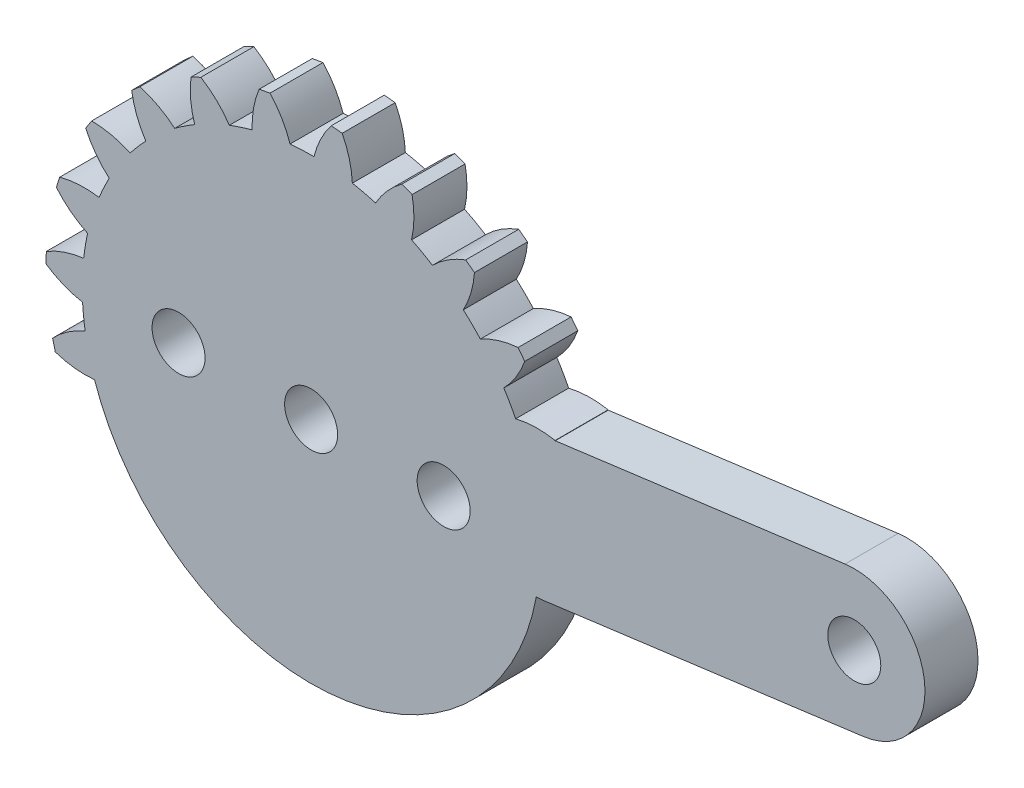
SolidWorks part; units mm, degrees
ref_plane "Front Plane" through (0, 0, 0) normal (0, 0, 1) x (1, 0, 0)
ref_plane "Top Plane" through (0, 0, 0) normal (0, 1, 0) x (1, 0, 0)
ref_plane "Right Plane" through (0, 0, 0) normal (1, 0, 0) x (0, 0, -1)
sketch "Sketch1" plane through (0, 0, 0) normal (0, 0, 1) x (1, 0, 0)
  line L0 (-15.3923, 0) -> (-14.8209, 0) construction
  line L1 (30.73, 4.05) -> (14.8179, 1.9551) construction
  line L2 (31.2521, 0.0842) -> (13.1979, -2.2927)
  line L3 (30.2079, 8.0158) -> (13.809, 5.8568)
  line L4 (0, 12.95) -> (0, -22.4393) construction
  line L5 (-34.6236, 0) -> (-14.8209, 0) construction
  line L6 (0, 0) -> (1.7567, 13.3438) construction
  line L7 (0, 0) -> (17.018, 13.0584) construction
  line L8 (12.0865, 8.8835) -> (11.709, 9.3754)
  line L9 (13.809, 5.8568) -> (13.8043, 5.8687)
  line L10 (-13.459, 0) -> (8.2812, 0) construction
  line L11 (-13.459, 0) -> (51.7251, 0) construction
  line L12 (1.9165, 14.5572) -> (2.6294, 19.9723) construction
  line L21 (-14.6251, -3.3328) -> (-14.4748, -3.9343)
  line L22 (-14.9819, 0.7366) -> (-14.9995, 0.1168)
  line L23 (-14.2276, 4.7513) -> (-14.4118, 4.1593)
  line L24 (-12.4181, 8.4137) -> (-12.7552, 7.8933)
  line L25 (-9.6876, 11.4521) -> (-10.1526, 11.0419)
  line L26 (-6.2387, 13.6411) -> (-6.797, 13.3716)
  line L27 (-2.327, 14.8184) -> (-2.9374, 14.7096)
  line L28 (1.7573, 14.8967) -> (1.1402, 14.9566)
  line L29 (5.7112, 13.8702) -> (5.1331, 14.0944)
  line L30 (9.2415, 11.815) -> (8.7454, 12.1868)
  line L33 (14.9427, 1.3103) -> (14.8757, 1.9267) [skipped]
  line L34 (14.7421, -2.7697) -> (14.8439, -2.1582) [skipped]
  line L35 (13.4481, -6.6444) -> (13.7112, -6.083) [skipped]
  line L36 (11.1568, -10.0263) -> (11.5616, -9.5567) [skipped]
  line L37 (8.038, -12.6645) -> (8.5545, -12.3215) [skipped]
  line L38 (4.3231, -14.3635) -> (4.913, -14.1726) [skipped]
  line L39 (0.2875, -14.9972) -> (0.9071, -14.9725) [skipped]
  line L40 (-3.7693, -14.5187) -> (-3.1661, -14.662) [skipped]
  line L41 (-7.5466, -12.9633) -> (-7.0045, -13.2641) [skipped]
  line L42 (-10.7643, -10.4466) -> (-10.3234, -10.8825) [skipped]
  line L43 (-13.1835, -7.155) -> (-12.8766, -7.6937) [skipped]
  circle A0 centre (0, 0) radius 1.5
  arc A1 (0.1616, 12.949) -> (-1.1918, 12.895) centre (0, 0) ccw
  arc A2 (12.0865, 8.8835) -> (11.709, 9.3754) centre (0, 0) ccw
  arc A3 (31.2521, 0.0842) -> (30.2079, 8.0158) centre (30.73, 4.05) ccw
  circle A5 centre (7.5, 0) radius 1.5
  circle A6 centre (-7.5, 0) radius 1.5
  arc A10 (9.5739, 8.7202) -> (11.709, 9.3754) centre (12.1467, 4.1425) cw
  arc A11 (10.901, 6.9907) -> (12.0865, 8.8835) centre (7.1452, 10.6606) ccw
  arc A12 (11.5716, 5.8139) -> (10.901, 6.9907) centre (0, 0) ccw
  arc A13 (11.5716, 5.8139) -> (13.8043, 5.8687) centre (12.8139, 0.7118) cw
  arc A14 (14.7633, -2.0866) -> (14.8439, -2.1582) centre (11.3183, -6.0497) cw
  arc A15 (-6.2387, 13.6411) -> (-6.797, 13.3716) centre (0, 0) ccw
  circle A16 centre (30.73, 4.05) radius 1.5
  arc A17 (13.8093, 5.8569) -> (13.8043, 5.8687) centre (0, 0) ccw
  arc A18 (14.8757, 1.9267) -> (14.8711, 1.9621) centre (0, 0) ccw
  arc A19 (9.2415, 11.815) -> (8.7454, 12.1868) centre (0, 0) ccw
  arc A20 (5.7112, 13.8702) -> (5.1331, 14.0944) centre (0, 0) ccw
  arc A21 (14.8439, -2.1582) -> (14.8559, -2.0744) centre (0, 0) ccw
  arc A28 (-14.6251, -3.3328) -> (-14.4748, -3.9343) centre (0, 0) ccw
  arc A29 (-14.9819, 0.7366) -> (-15, 0) centre (0, 0) ccw
  arc A30 (3.6492, 12.4252) -> (2.3314, 12.7384) centre (0, 0) ccw
  arc A31 (-14.2276, 4.7513) -> (-14.4118, 4.1593) centre (0, 0) ccw
  arc A32 (6.8662, 10.9799) -> (5.6818, 11.637) centre (0, 0) ccw
  arc A33 (9.5739, 8.7202) -> (8.6107, 9.6726) centre (0, 0) ccw
  arc A34 (-9.6876, 11.4521) -> (-10.1526, 11.0419) centre (0, 0) ccw
  arc A35 (12.7393, -2.3264) -> (13.1979, -2.2927) centre (12.6758, 1.6731) ccw
  arc A36 (-12.7837, -2.069) -> (-14.6251, -3.3328) centre (-10.8008, -6.9314) ccw
  arc A37 (-12.2555, -4.184) -> (-14.4748, -3.9343) centre (-12.7915, 1.0397) cw
  arc A38 (-12.8678, 1.4567) -> (-14.9819, 0.7366) centre (-12.2704, -3.7603) ccw
  arc A39 (-12.9298, -0.7224) -> (-14.9995, 0.1168) centre (-12.0366, 4.4522) cw
  arc A40 (-11.9976, 4.8744) -> (-14.2276, 4.7513) centre (-12.8299, -0.3104) ccw
  arc A41 (-12.6453, 2.7928) -> (-14.4118, 4.1593) centre (-10.3891, 7.5346) cw
  arc A42 (-10.2376, 7.9306) -> (-12.4181, 8.4137) centre (-12.4379, 3.1626) ccw
  arc A43 (-11.4229, 6.1009) -> (-12.7552, 7.8933) centre (-7.971, 10.0581) cw
  arc A44 (-7.7183, 10.3985) -> (-9.6876, 11.4521) centre (-11.1234, 6.401) ccw
  arc A45 (-9.3533, 8.9565) -> (-10.1526, 11.0419) centre (-4.9618, 11.8357) cw
  arc A46 (-4.6266, 12.0953) -> (-6.2387, 13.6411) centre (-8.9839, 9.1647) ccw
  arc A47 (-6.59, 11.1479) -> (-6.797, 13.3716) centre (-1.5846, 12.7355) cw
  arc A48 (-1.1918, 12.895) -> (-2.327, 14.8184) centre (-6.1782, 11.2487) ccw
  arc A49 (-3.3379, 12.5124) -> (-2.9374, 14.7096) centre (1.9102, 12.6907) cw
  arc A50 (2.3314, 12.7384) -> (1.7573, 14.8967) centre (-2.9142, 12.4984) ccw
  arc A51 (0.1616, 12.949) -> (1.1402, 14.9566) centre (5.2632, 11.7047) cw
  arc A52 (5.6818, 11.637) -> (5.7112, 13.8702) centre (0.5659, 12.8212) ccw
  arc A53 (3.6492, 12.4252) -> (5.1331, 14.0944) centre (8.226, 9.8507) cw
  arc A54 (8.6107, 9.6726) -> (9.2415, 11.815) centre (4.004, 12.1931) ccw
  arc A55 (6.8662, 10.9799) -> (8.7454, 12.1868) centre (10.5786, 7.2661) cw
  arc A56 (-3.3379, 12.5124) -> (-4.6266, 12.0953) centre (0, 0) ccw
  arc A57 (-6.59, 11.1479) -> (-7.7183, 10.3985) centre (0, 0) ccw
  arc A58 (-9.3533, 8.9565) -> (-10.2376, 7.9306) centre (0, 0) ccw
  arc A59 (-11.4229, 6.1009) -> (-11.9976, 4.8744) centre (0, 0) ccw
  arc A60 (-12.6453, 2.7928) -> (-12.8678, 1.4567) centre (0, 0) ccw
  arc A61 (-12.9298, -0.7224) -> (-12.7837, -2.069) centre (0, 0) ccw
  arc A62 (-12.2555, -4.184) -> (12.7393, -2.3264) centre (0, 0) ccw
  arc A63 (-11.7514, -5.4413) -> (-12.1518, -5.7859) centre (-8.5302, -9.5884) ccw [skipped]
  arc A64 (-10.6722, -7.3354) -> (-11.1728, -7.5041) centre (-12.5976, -2.45) cw [skipped]
  arc A65 (-9.8476, -8.41) -> (-10.1402, -8.8499) centre (-5.627, -11.5343) ccw [skipped]
  arc A66 (-8.7339, -10.2402) -> (-10.3234, -10.8825) centre (-11.4695, -5.7579) cw [skipped]
  arc A67 (-7.3765, -11.2575) -> (-7.5466, -12.9633) centre (-2.3064, -12.6247) ccw [skipped]
  arc A68 (12.3829, 3.7904) -> (12.8265, 4.0774) centre (9.7564, 8.3376) ccw [skipped]
  arc A69 (14.8179, 1.9551) -> (14.8757, 1.9267) centre (12.5308, -2.7718) cw
  arc A70 (12.711, 2.4763) -> (13.2375, 2.4316) centre (12.5308, -2.7718) cw [skipped]
  arc A71 (12.9463, 0.309) -> (13.4509, 0.4656) centre (11.6441, 5.3961) ccw [skipped]
  arc A72 (12.9078, -1.0449) -> (13.4026, -1.23) centre (11.3183, -6.0497) cw [skipped]
  arc A73 (12.5496, -3.1953) -> (13.0777, -3.1806) centre (12.6681, 2.0545) ccw [skipped]
  arc A74 (-5.3072, -11.8126) -> (-5.6472, -12.2169) centre (-9.4907, -8.6388) cw [skipped]
  arc A75 (-4.0443, -12.3023) -> (-4.0657, -12.8302) centre (1.1852, -12.7788) ccw [skipped]
  arc A76 (-1.9234, -12.8064) -> (-2.1418, -13.2875) centre (-6.808, -10.879) cw [skipped]
  arc A77 (12.1472, -4.4887) -> (12.5738, -4.8004) centre (9.2664, -8.879) cw [skipped]
  arc A78 (11.2221, -6.4627) -> (11.7346, -6.591) centre (12.7527, -1.4395) ccw [skipped]
  arc A79 (10.8124, -8.0147) -> (11.5616, -9.5567) centre (6.5272, -11.0498) cw [skipped]
  arc A80 (9.0624, -9.2507) -> (9.5213, -9.5126) centre (11.8914, -4.8268) ccw [skipped]
  arc A81 (8.2491, -10.6347) -> (8.5545, -12.3215) centre (3.304, -12.4011) cw [skipped]
  arc A82 (6.2305, -11.3527) -> (6.6017, -11.7286) centre (10.1482, -7.856) ccw [skipped]
  arc A83 (5.074, -12.4659) -> (4.913, -14.1726) centre (-0.1643, -12.8326) cw [skipped]
  arc A84 (3.1926, -13.0748) -> (4.3231, -14.3635) centre (7.6523, -10.3026) ccw [skipped]
  arc A85 (-0.5752, -12.9372) -> (-0.4534, -13.4513) centre (4.5889, -11.9852) ccw [skipped]
  arc A86 (1.6031, -12.8504) -> (1.5226, -13.3726) centre (-3.6204, -12.3124) cw [skipped]
  arc A87 (-12.4181, 8.4137) -> (-12.7552, 7.8933) centre (0, 0) ccw
  arc A88 (1.9579, 14.8717) -> (1.1402, 14.9566) centre (0, 0) ccw
  arc A89 (-2.327, 14.8184) -> (-2.9374, 14.7096) centre (0, 0) ccw
  arc A91 (0.3125, 13.4553) -> (0, 13.459) centre (0, 0) ccw construction
  point P9 (21.7029, 2.8616)
  point P26 (0, 0)
  dimension "D1" = 3
  dimension "D2" = 25.9
  dimension "D3" = 30
  dimension "D12" = 37.5
  dimension "D7" = 3
  dimension "D4" = 7.5
  dimension "D5" = 15
  dimension "D6" = 23.23
  dimension "D8" = 8
  dimension "D9" = 7.5
  dimension "D10" = 4.05
  dimension "D11" = 7.5
  dimension "D13" = 0.31
  dimension "D14" = 1.09
  dimension "D15" = 23
extrude "Boss-Extrude1" add sketch "Sketch1" along normal blind 3
